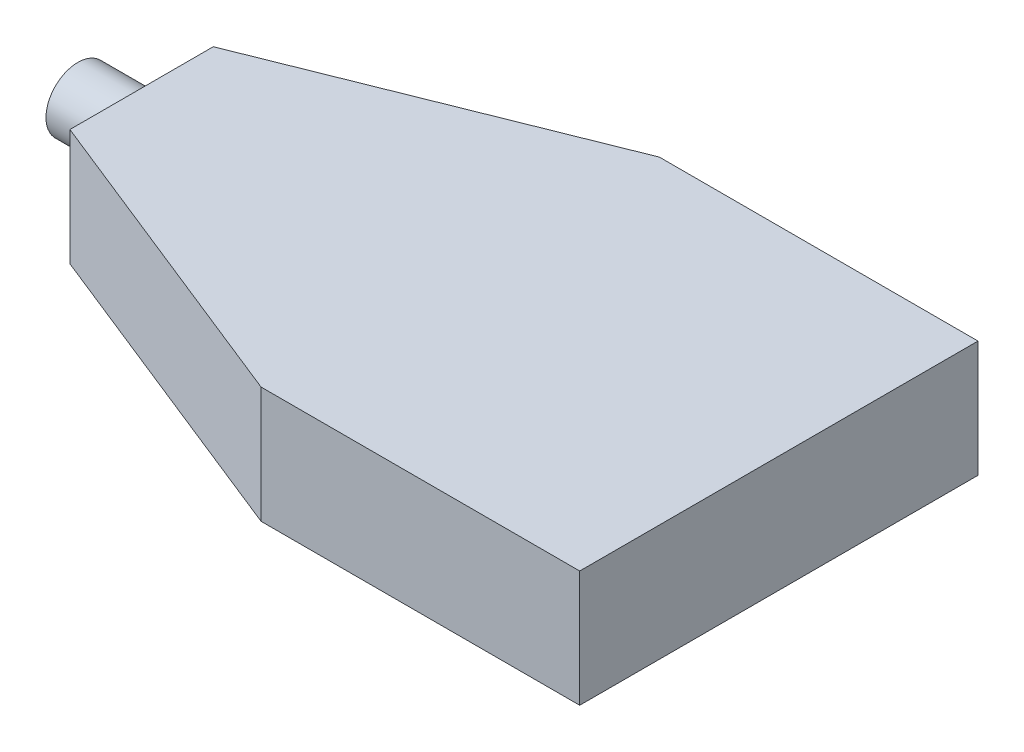
SolidWorks part; units mm, degrees
ref_plane "Front Plane" through (0, 0, 0) normal (0, 0, 1) x (1, 0, 0)
ref_plane "Top Plane" through (0, 0, 0) normal (0, 1, 0) x (1, 0, 0)
ref_plane "Right Plane" through (0, 0, 0) normal (1, 0, 0) x (0, 0, -1)
sketch "Sketch1" plane through (0, 0, 0) normal (0, 1, 0) x (1, 0, 0)
  line L0 (-50, 0) -> (-150, 0) construction
  line L1 (-50, -62.5) -> (50, -62.5)
  line L2 (-50, -62.5) -> (-50, 62.5)
  line L3 (-50, 62.5) -> (50, 62.5)
  line L4 (50, -62.5) -> (50, 62.5)
  line L5 (-50, -62.5) -> (50, 62.5) construction
  line L6 (-50, 62.5) -> (50, -62.5) construction
  line L7 (-150, 22.5) -> (-150, -22.5)
  line L8 (-150, 22.5) -> (-50, 62.5)
  line L9 (-150, -22.5) -> (-50, -62.5)
  point P0 (0, 0)
  point P11 (-150, 0)
  dimension "D1" = 100
  dimension "D2" = 125
  dimension "D3" = 100
  dimension "D4" = 45
extrude "Boss-Extrude1" add sketch "Sketch1" along normal blind 36.5 contours L7 L9 L2 L8 | L1 L4 L3 L2
sketch "Sketch27" plane through (-150, 0, 0) normal (-1, 0, 0) x (0, 0, 1)
  line L0 (0, 36.5) -> (0, 23.5)
  line L1 (-22.5, 36.5) -> (22.5, 36.5) construction
  circle A0 centre (0, 23.5) radius 10
  dimension "D1" = 13
extrude "Boss-Extrude2" add sketch "Sketch27" along normal blind 20
sketch "Sketch28" plane through (-170, 0, 0) normal (-1, 0, 0) x (0, 0, 1)
  circle A0 centre (0, 23.5) radius 9.1
extrude "Cut-Extrude11" cut sketch "Sketch28" against normal blind 20
